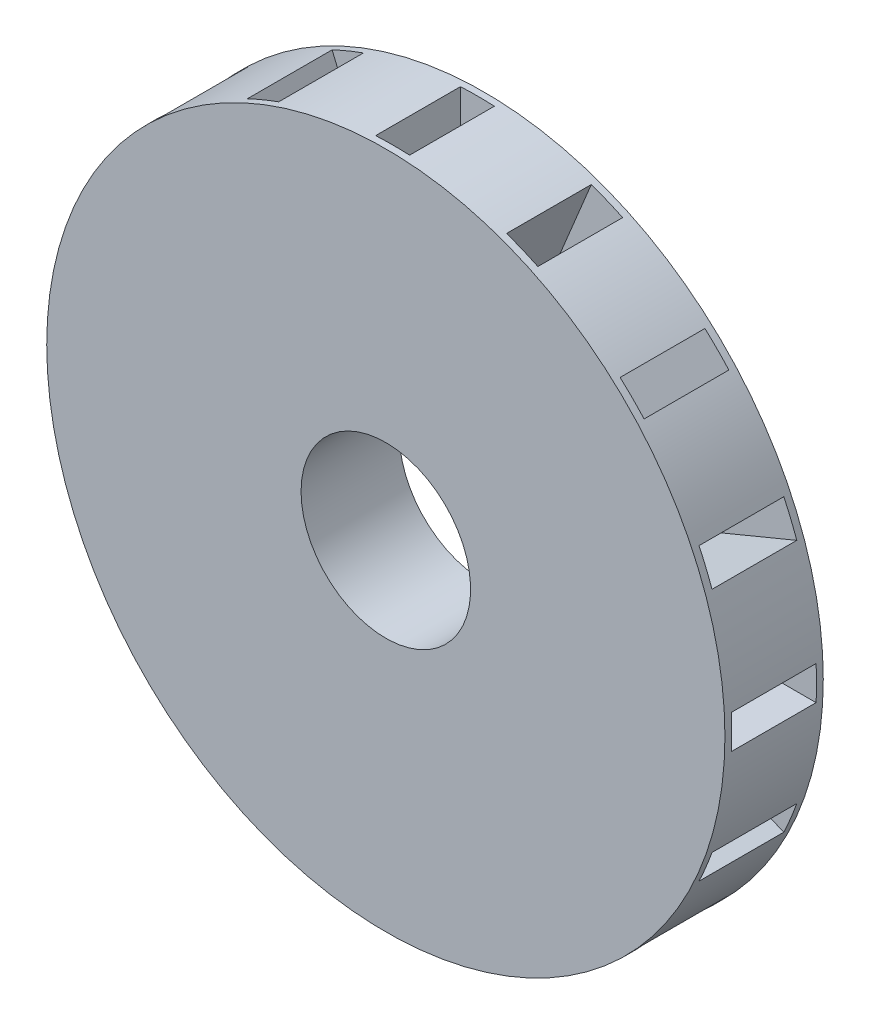
SolidWorks part; units mm, degrees
ref_plane "Front Plane" through (0, 0, 0) normal (0, 0, 1) x (1, 0, 0)
ref_plane "Top Plane" through (0, 0, 0) normal (0, 1, 0) x (1, 0, 0)
ref_plane "Right Plane" through (0, 0, 0) normal (1, 0, 0) x (0, 0, -1)
sketch "Sketch1" plane through (0, 0, 0) normal (0, 0, 1) x (1, 0, 0)
  circle A0 centre (0, 0) radius 100
  circle A1 centre (0, 0) radius 25
  dimension "D1" = 200
  dimension "D2" = 50
extrude "Boss-Extrude1" add sketch "Sketch1" along normal mid plane 29
sketch "Sketch2" plane through (0, 0, 0) normal (0, 0, 1) x (1, 0, 0)
  line L0 (-154.614, 0) -> (154.614, 0) construction
  line L1 (0, -124.2574) -> (0, 124.2574) construction
  line L2 (100, -103.014) -> (100, 103.014) construction
  line L3 (60, -107.033) -> (60, 107.033) construction
  line L4 (100, 5) -> (110, -5)
  line L5 (60, -5) -> (100, -5)
  line L6 (60, -5) -> (60, 5)
  line L7 (60, 5) -> (100, 5)
  line L8 (100, -5) -> (100, 5) construction
  line L9 (60, -5) -> (100, 5) construction
  line L10 (60, 5) -> (100, -5) construction
  line L11 (110, -5) -> (100, -5)
  line L12 (90.4745, -42.8877) -> (94.3014, -33.6489) construction
  line L13 (57.3462, -18.3416) -> (94.3014, -33.6489)
  line L14 (53.5194, -27.5804) -> (57.3462, -18.3416)
  line L15 (53.5194, -27.5804) -> (90.4745, -42.8877)
  line L16 (99.7133, -46.7146) -> (90.4745, -42.8877)
  line L17 (94.3014, -33.6489) -> (99.7133, -46.7146)
  line L18 (67.1751, -74.2462) -> (74.2462, -67.1751) construction
  line L19 (45.9619, -38.8909) -> (74.2462, -67.1751)
  line L20 (38.8909, -45.9619) -> (45.9619, -38.8909)
  line L21 (38.8909, -45.9619) -> (67.1751, -74.2462)
  line L22 (74.2462, -81.3173) -> (67.1751, -74.2462)
  line L23 (74.2462, -67.1751) -> (74.2462, -81.3173)
  line L24 (33.6489, -94.3014) -> (42.8877, -90.4745) construction
  line L25 (27.5804, -53.5194) -> (42.8877, -90.4745)
  line L26 (18.3416, -57.3462) -> (27.5804, -53.5194)
  line L27 (18.3416, -57.3462) -> (33.6489, -94.3014)
  line L28 (37.4758, -103.5402) -> (33.6489, -94.3014)
  line L29 (42.8877, -90.4745) -> (37.4758, -103.5402)
  line L30 (-5, -100) -> (5, -100) construction
  line L31 (5, -60) -> (5, -100)
  line L32 (-5, -60) -> (5, -60)
  line L33 (-5, -60) -> (-5, -100)
  line L34 (-5, -110) -> (-5, -100)
  line L35 (5, -100) -> (-5, -110)
  line L36 (-42.8877, -90.4745) -> (-33.6489, -94.3014) construction
  line L37 (-18.3416, -57.3462) -> (-33.6489, -94.3014)
  line L38 (-27.5804, -53.5194) -> (-18.3416, -57.3462)
  line L39 (-27.5804, -53.5194) -> (-42.8877, -90.4745)
  line L40 (-46.7146, -99.7133) -> (-42.8877, -90.4745)
  line L41 (-33.6489, -94.3014) -> (-46.7146, -99.7133)
  line L42 (-74.2462, -67.1751) -> (-67.1751, -74.2462) construction
  line L43 (-38.8909, -45.9619) -> (-67.1751, -74.2462)
  line L44 (-45.9619, -38.8909) -> (-38.8909, -45.9619)
  line L45 (-45.9619, -38.8909) -> (-74.2462, -67.1751)
  line L46 (-81.3173, -74.2462) -> (-74.2462, -67.1751)
  line L47 (-67.1751, -74.2462) -> (-81.3173, -74.2462)
  line L48 (-94.3014, -33.6489) -> (-90.4745, -42.8877) construction
  line L49 (-53.5194, -27.5804) -> (-90.4745, -42.8877)
  line L50 (-57.3462, -18.3416) -> (-53.5194, -27.5804)
  line L51 (-57.3462, -18.3416) -> (-94.3014, -33.6489)
  line L52 (-103.5402, -37.4758) -> (-94.3014, -33.6489)
  line L53 (-90.4745, -42.8877) -> (-103.5402, -37.4758)
  line L54 (-100, 5) -> (-100, -5) construction
  line L55 (-60, -5) -> (-100, -5)
  line L56 (-60, 5) -> (-60, -5)
  line L57 (-60, 5) -> (-100, 5)
  line L58 (-110, 5) -> (-100, 5)
  line L59 (-100, -5) -> (-110, 5)
  line L60 (-90.4745, 42.8877) -> (-94.3014, 33.6489) construction
  line L61 (-57.3462, 18.3416) -> (-94.3014, 33.6489)
  line L62 (-53.5194, 27.5804) -> (-57.3462, 18.3416)
  line L63 (-53.5194, 27.5804) -> (-90.4745, 42.8877)
  line L64 (-99.7133, 46.7146) -> (-90.4745, 42.8877)
  line L65 (-94.3014, 33.6489) -> (-99.7133, 46.7146)
  line L66 (-67.1751, 74.2462) -> (-74.2462, 67.1751) construction
  line L67 (-45.9619, 38.8909) -> (-74.2462, 67.1751)
  line L68 (-38.8909, 45.9619) -> (-45.9619, 38.8909)
  line L69 (-38.8909, 45.9619) -> (-67.1751, 74.2462)
  line L70 (-74.2462, 81.3173) -> (-67.1751, 74.2462)
  line L71 (-74.2462, 67.1751) -> (-74.2462, 81.3173)
  line L72 (-33.6489, 94.3014) -> (-42.8877, 90.4745) construction
  line L73 (-27.5804, 53.5194) -> (-42.8877, 90.4745)
  line L74 (-18.3416, 57.3462) -> (-27.5804, 53.5194)
  line L75 (-18.3416, 57.3462) -> (-33.6489, 94.3014)
  line L76 (-37.4758, 103.5402) -> (-33.6489, 94.3014)
  line L77 (-42.8877, 90.4745) -> (-37.4758, 103.5402)
  line L78 (5, 100) -> (-5, 100) construction
  line L79 (-5, 60) -> (-5, 100)
  line L80 (5, 60) -> (-5, 60)
  line L81 (5, 60) -> (5, 100)
  line L82 (5, 110) -> (5, 100)
  line L83 (-5, 100) -> (5, 110)
  line L84 (42.8877, 90.4745) -> (33.6489, 94.3014) construction
  line L85 (18.3416, 57.3462) -> (33.6489, 94.3014)
  line L86 (27.5804, 53.5194) -> (18.3416, 57.3462)
  line L87 (27.5804, 53.5194) -> (42.8877, 90.4745)
  line L88 (46.7146, 99.7133) -> (42.8877, 90.4745)
  line L89 (33.6489, 94.3014) -> (46.7146, 99.7133)
  line L90 (74.2462, 67.1751) -> (67.1751, 74.2462) construction
  line L91 (38.8909, 45.9619) -> (67.1751, 74.2462)
  line L92 (45.9619, 38.8909) -> (38.8909, 45.9619)
  line L93 (45.9619, 38.8909) -> (74.2462, 67.1751)
  line L94 (81.3173, 74.2462) -> (74.2462, 67.1751)
  line L95 (67.1751, 74.2462) -> (81.3173, 74.2462)
  line L96 (94.3014, 33.6489) -> (90.4745, 42.8877) construction
  line L97 (53.5194, 27.5804) -> (90.4745, 42.8877)
  line L98 (57.3462, 18.3416) -> (53.5194, 27.5804)
  line L99 (57.3462, 18.3416) -> (94.3014, 33.6489)
  line L100 (103.5402, 37.4758) -> (94.3014, 33.6489)
  line L101 (90.4745, 42.8877) -> (103.5402, 37.4758)
  point P0 (80, 0)
  point P5 (0, 0)
  point P9 (0, 0)
  point P12 (100, 0)
  point P15 (60, 0)
  point P98 (0, 0)
  dimension "D1" = 60
  dimension "D2" = 100
  dimension "D3" = 80
  dimension "D4" = 10
  dimension "D5" = 40
  dimension "D6" = 10
  dimension "D7" = 16
extrude "Cut-Extrude1" cut sketch "Sketch2" against normal mid plane 25
